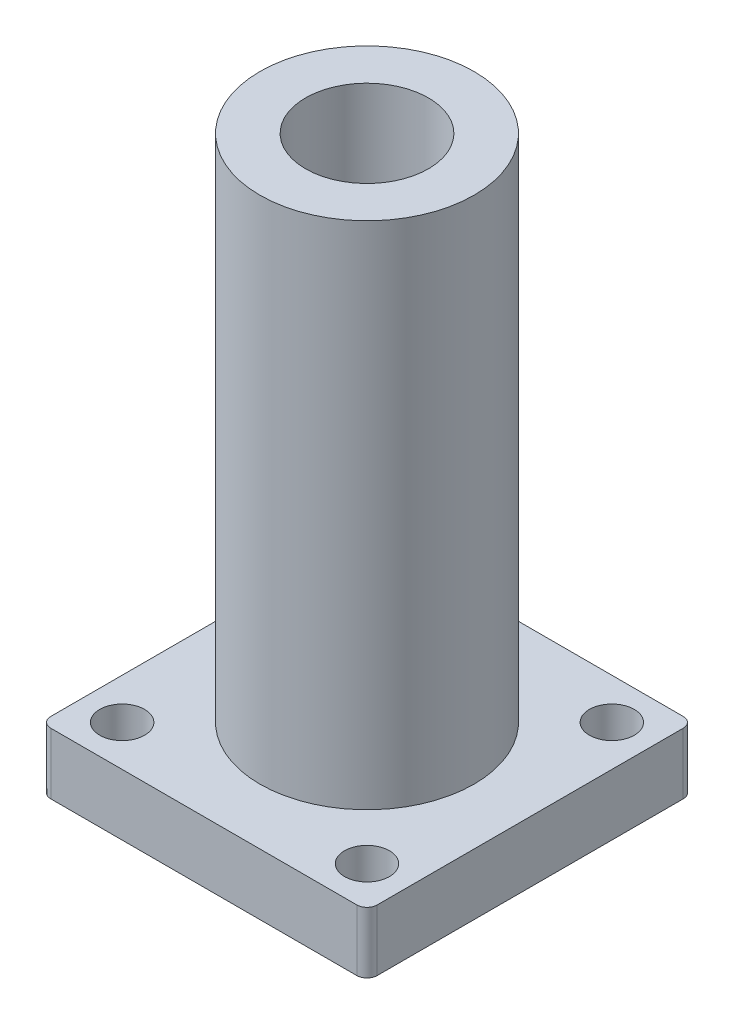
SolidWorks part; units mm, degrees
ref_plane "Front Plane" through (0, 0, 0) normal (0, 0, 1) x (1, 0, 0)
ref_plane "Top Plane" through (0, 0, 0) normal (0, 1, 0) x (1, 0, 0)
ref_plane "Right Plane" through (0, 0, 0) normal (1, 0, 0) x (0, 0, -1)
ref_plane "Plane1" through (0, 0, 0) normal (0, -1, 0) x (1, 0, 0)
sketch "Sketch1" plane through (0, 0, 0) normal (0, -1, 0) x (1, 0, 0)
  line L0 (32, -32) -> (32, 0)
  line L1 (32, 0) -> (0, 0)
  line L2 (0, 0) -> (0, -32)
  line L3 (0, -32) -> (32, -32)
extrude "Boss-Extrude1" add sketch "Sketch1" against normal blind 6
ref_plane "Plane2" through (0, 0, -16) normal (0, 0, -1) x (-1, 0, 0)
sketch "Sketch2" plane through (0, 0, -16) normal (0, 0, -1) x (-1, 0, 0)
  line L0 (-26.5, 6) -> (-16, 6)
  line L1 (-16, 6) -> (-16, 56)
  line L2 (-16, 56) -> (-26.5, 56)
  line L3 (-26.5, 56) -> (-26.5, 6)
  line L4 (-16, 6) -> (-16, 56) construction
  line L5 (0, 6) -> (-32, 6) construction
  dimension "D1" = 10.5
  dimension "D2" = 50
  dimension "D3" = 0
revolve "Revolve1" add sketch "Sketch2" angle 360 about L4
hole_wizard "Ø4.4 (4.4) Diameter Hole1" positions "Sketch4" profile "Sketch3" hole size "Ø4.4" standard "ANSI Metric"
sketch "Sketch4" plane through (0, 0, 0) normal (0, -1, 0) x (-1, 0, 0)
  point P0 (-28, 4)
  point P1 (-28, 28)
  point P2 (-4, 4)
  point P3 (-4, 28)
sketch "Sketch3" plane through (28, 0, -4) normal (1, 0, 0) x (0, 0, -1)
  line L0 (0, 0) -> (0, 56)
  line L1 (0, 56) -> (2.2, 56)
  line L2 (2.2, 56) -> (2.2, 0)
  line L5 (2.2, 0) -> (0, 0)
  line L11 (0, -6.35) -> (0, 107.95) construction
  dimension "Thru Hole Dia." = 4.4
  dimension "Thru Hole Depth" = 56
hole_wizard "Hole1" positions "Sketch6" profile "Sketch5" legacy end condition through all
sketch "Sketch6" plane through (0, 56, 0) normal (0, 1, 0) x (1, 0, 0)
  point P0 (16, 16)
sketch "Sketch5" plane through (16, 56, -16) normal (1, 0, 0) x (0, 0, 1)
  line L0 (0, 0) -> (0, 56)
  line L1 (0, 56) -> (6.025, 56)
  line L2 (6.025, 56) -> (6.025, 0)
  line L3 (6.025, 0) -> (0, 0)
  line L4 (0, 110) -> (0, -10) construction
  dimension "Diameter" = 12.05
  dimension "Depth" = 56
fillet "Fillet1" radius 1 4 edges at (32, 3, 0) (32, 3, -32) (0, 3, -32) (0, 3, 0)
